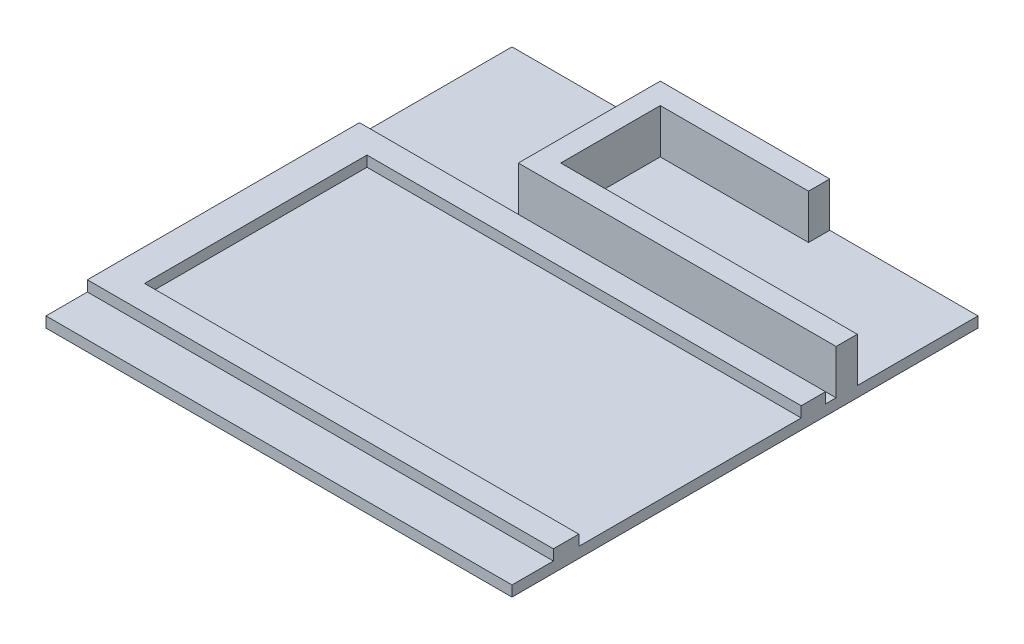
SolidWorks part; units mm, degrees
ref_plane "Front Plane" through (0, 0, 0) normal (0, 0, 1) x (1, 0, 0)
ref_plane "Top Plane" through (0, 0, 0) normal (0, 1, 0) x (1, 0, 0)
ref_plane "Right Plane" through (0, 0, 0) normal (1, 0, 0) x (0, 0, -1)
sketch "Sketch1" plane through (0, 0, 0) normal (0, 1, 0) x (1, 0, 0)
  line L1 (-110, -110) -> (110, -110)
  line L2 (-110, -110) -> (-110, 110)
  line L3 (-110, 110) -> (110, 110)
  line L4 (110, -110) -> (110, 110)
  line L5 (-110, -110) -> (110, 110) construction
  line L6 (-110, 110) -> (110, -110) construction
  point P0 (0, 0)
  dimension "D1" = 220
  dimension "D2" = 220
extrude "Boss-Extrude1" add sketch "Sketch1" along normal blind 5
sketch "Sketch2" plane through (0, 5, 0) normal (0, 1, 0) x (1, 0, 0)
  line L0 (-110, 110) -> (-40, 110) construction
  line L1 (110, 110) -> (-110, 110) construction
  line L2 (-40, 110) -> (40, 110)
  line L3 (40, 110) -> (40, 100)
  line L4 (40, 100) -> (-30, 100)
  line L5 (-30, 100) -> (-30, 53)
  line L6 (-30, 53) -> (110, 53)
  line L7 (110, 53) -> (110, 43)
  line L8 (110, -110) -> (110, 110) construction
  line L9 (110, 43) -> (-40, 43)
  line L10 (-40, 43) -> (-40, 110)
extrude "Boss-Extrude2" add sketch "Sketch2" along normal blind 21
sketch "Sketch3" plane through (0, 5, 0) normal (0, 1, 0) x (1, 0, 0)
  line L0 (-110, 110) -> (-110, 38) construction
  line L2 (-110, 110) -> (-110, -110) construction
  line L3 (-110, 38) -> (110, 38)
  line L4 (110, -110) -> (110, 43) construction
  line L5 (110, 38) -> (110, 26.5325)
  line L6 (110, 26.5325) -> (-95, 26.5325)
  line L7 (-95, 26.5325) -> (-95, -78.4675)
  line L8 (-95, -78.4675) -> (110, -78.4675)
  line L9 (110, -78.4675) -> (110, -90.4675)
  line L10 (110, -90.4675) -> (-110, -90.4675)
  line L11 (-110, -90.4675) -> (-110, 38)
extrude "Boss-Extrude3" add sketch "Sketch3" along normal blind 5
